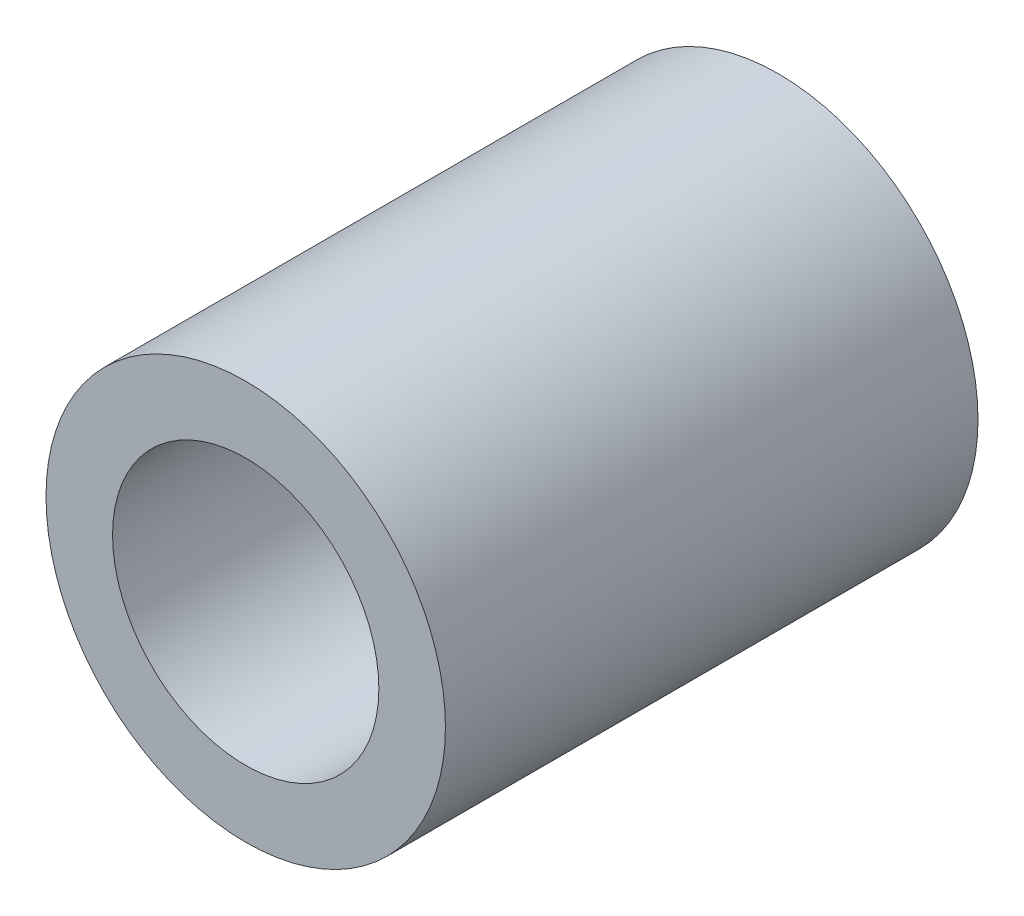
SolidWorks part; units mm, degrees
material "Brass"
ref_plane "Front" through (0, 0, 0) normal (0, 0, 1) x (1, 0, 0)
ref_plane "Top" through (0, 0, 0) normal (0, 1, 0) x (1, 0, 0)
ref_plane "Right" through (0, 0, 0) normal (1, 0, 0) x (0, 0, -1)
sketch "Sketch1" plane through (0, 0, 0) normal (0, 0, 1) x (1, 0, 0)
  circle A0 centre (0, 0) radius 9.525
  circle A1 centre (0, 0) radius 6.35
  dimension "D1" = 19.05
  dimension "D2" = 12.7
extrude "Boss-Extrude1" add sketch "Sketch1" against normal blind 25.4
